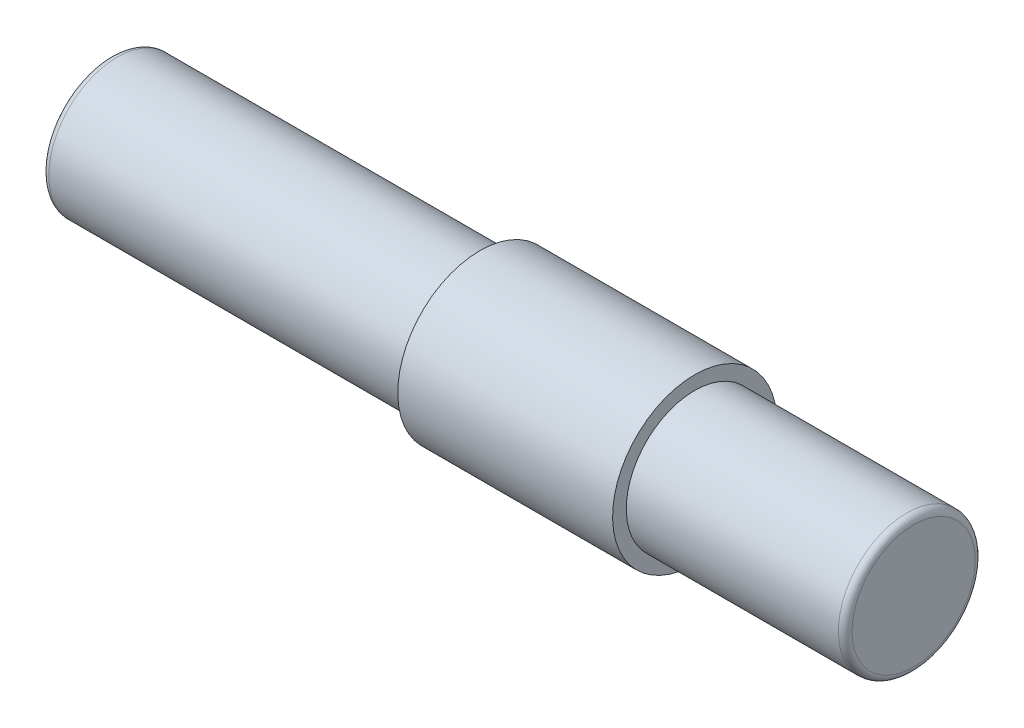
SolidWorks part; units mm, degrees
material "1.5714 (16NiCr4)"
ref_plane "Ebene vorne" through (0, 0, 0) normal (0, 0, 1) x (1, 0, 0)
ref_plane "Ebene oben" through (0, 0, 0) normal (0, 1, 0) x (1, 0, 0)
ref_plane "Ebene rechts" through (0, 0, 0) normal (1, 0, 0) x (0, 0, -1)
sketch "Skizze1" plane through (0, 0, 0) normal (0, 0, 1) x (1, 0, 0)
  line L0 (-78.7781, 1.7544) -> (-78.7781, 6.7544)
  line L1 (-78.7781, 6.7544) -> (-51.7781, 6.7544)
  line L2 (-51.7781, 6.7544) -> (-51.7781, 7.7544)
  line L3 (-51.7781, 7.7544) -> (-36.0781, 7.7544)
  line L4 (-36.0781, 7.7544) -> (-36.0781, 6.7544)
  line L5 (-36.0781, 6.7544) -> (-26.0781, 6.7544)
  line L6 (-20.0781, 6.7544) -> (-20.0781, 1.7544)
  line L7 (-20.0781, 1.7544) -> (-78.7781, 1.7544)
  line L11 (-25.0781, 6.7544) -> (-20.0781, 6.7544)
  line L12 (-26.0781, 6.7544) -> (-25.0781, 6.7544)
  dimension "D1" = 5
  dimension "D2" = 15.7
  dimension "D3" = 27
  dimension "D4" = 16
  dimension "D5" = 6
  dimension "D6" = 5
revolve "Rotation1" add sketch "Skizze1" angle 360 about L7
fillet "Verrundung1" radius 0.5 2 edges at (-78.7781, 6.7544, 0) (-20.0781, 6.7544, 0)
